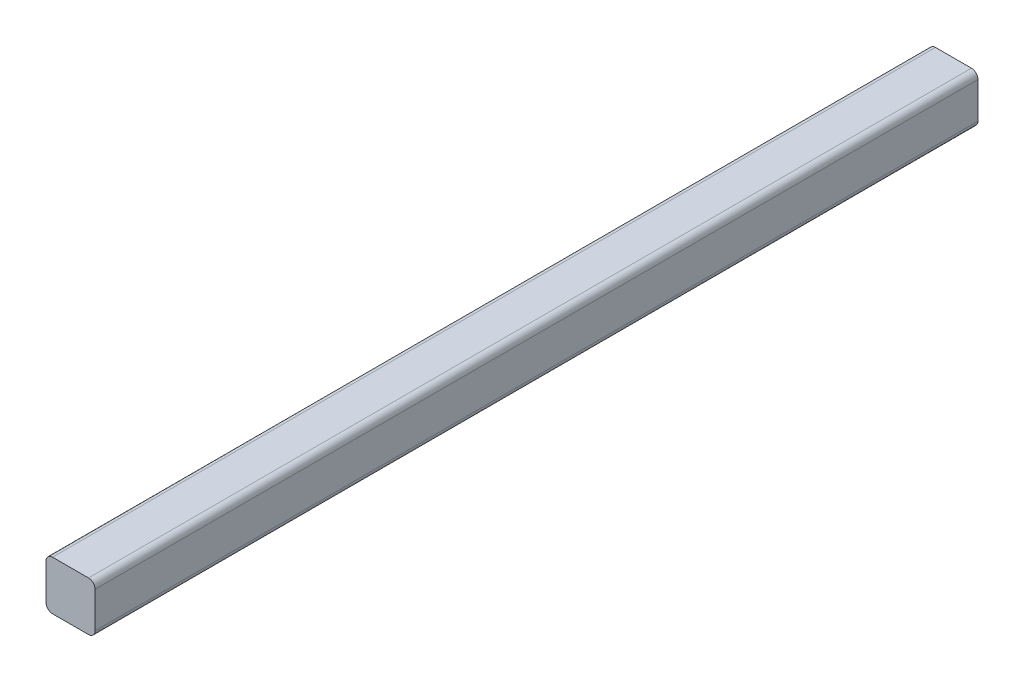
SolidWorks part; units mm, degrees
ref_plane "Front Plane" through (0, 0, 0) normal (0, 0, 1) x (1, 0, 0)
ref_plane "Top Plane" through (0, 0, 0) normal (0, 1, 0) x (1, 0, 0)
ref_plane "Right Plane" through (0, 0, 0) normal (1, 0, 0) x (0, 0, -1)
sketch "Sketch1" plane through (0, 0, 0) normal (0, 0, 1) x (1, 0, 0)
  line L1 (-9.525, -9.525) -> (9.525, -9.525)
  line L2 (-9.525, -9.525) -> (-9.525, 9.525)
  line L3 (-9.525, 9.525) -> (9.525, 9.525)
  line L4 (9.525, -9.525) -> (9.525, 9.525)
  line L5 (-9.525, -9.525) -> (9.525, 9.525) construction
  line L6 (-9.525, 9.525) -> (9.525, -9.525) construction
  point P0 (0, 0)
  dimension "D1" = 19.05
extrude "Boss-Extrude1" add sketch "Sketch1" along normal mid plane 342.9
fillet "Fillet1" radius 2.54 4 edges at (9.525, 9.525, 0) (-9.525, 9.525, 0) (-9.525, -9.525, 0) (9.525, -9.525, 0)
